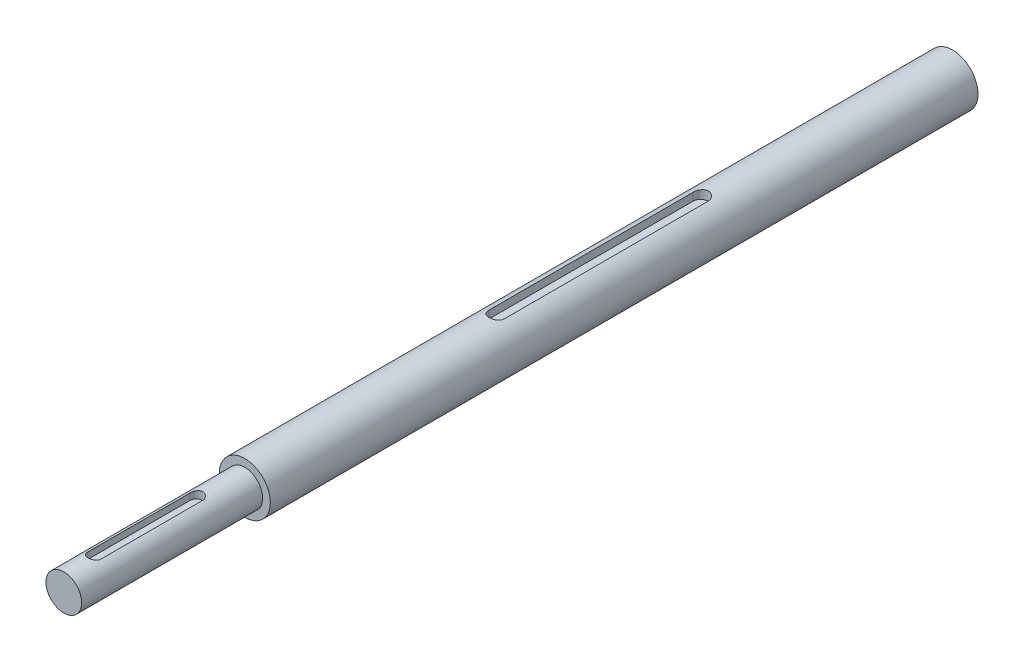
SolidWorks part; units mm, degrees
ref_plane "Ön Düzlem" through (0, 0, 0) normal (0, 0, 1) x (1, 0, 0)
ref_plane "Üst Düzlem" through (0, 0, 0) normal (0, 1, 0) x (1, 0, 0)
ref_plane "Sağ Düzlem" through (0, 0, 0) normal (1, 0, 0) x (0, 0, -1)
sketch "Sketch1" plane through (0, 0, 0) normal (0, 0, 1) x (1, 0, 0)
  circle A0 centre (0, 0) radius 10
  dimension "D1" = 20
extrude "Boss-Extrude1" add sketch "Sketch1" along normal mid plane 277.6
sketch "Sketch2" plane through (0, 0, 138.8) normal (0, 0, 1) x (1, 0, 0)
  circle A0 centre (0, 0) radius 7
  dimension "D1" = 14
extrude "Boss-Extrude2" add sketch "Sketch2" along normal blind 71
ref_plane "Plane2" through (0, 7, 0) normal (0, 1, 0) x (1, 0, 0)
sketch "Sketch4" plane through (0, 7, 0) normal (0, 1, 0) x (1, 0, 0)
  line L0 (0, -197.8) -> (0, -157.8) construction
  line L1 (-2.5, -197.8) -> (-2.5, -157.8)
  line L2 (2.5, -197.8) -> (2.5, -157.8)
  line L3 (-7, -209.8) -> (7, -209.8) construction
  arc A0 (-2.5, -197.8) -> (2.5, -197.8) centre (0, -197.8) ccw
  arc A1 (2.5, -157.8) -> (-2.5, -157.8) centre (0, -157.8) ccw
  point P3 (0, -177.8)
  dimension "D1" = 5
  dimension "D2" = 12
  dimension "D3" = 40
extrude "Cut-Extrude1" cut sketch "Sketch4" against normal blind 3
ref_plane "Plane3" through (0, 10, 0) normal (0, 1, 0) x (1, 0, 0)
sketch "Sketch5" plane through (0, 10, 0) normal (0, 1, 0) x (1, 0, 0)
  line L0 (0, -40) -> (0, 40) construction
  line L1 (-3, -40) -> (-3, 40)
  line L2 (3, -40) -> (3, 40)
  arc A0 (-3, -40) -> (3, -40) centre (0, -40) ccw
  arc A1 (3, 40) -> (-3, 40) centre (0, 40) ccw
  point P2 (0, 0)
  dimension "D1" = 80
  dimension "D2" = 6
extrude "Cut-Extrude2" cut sketch "Sketch5" against normal blind 3.5
